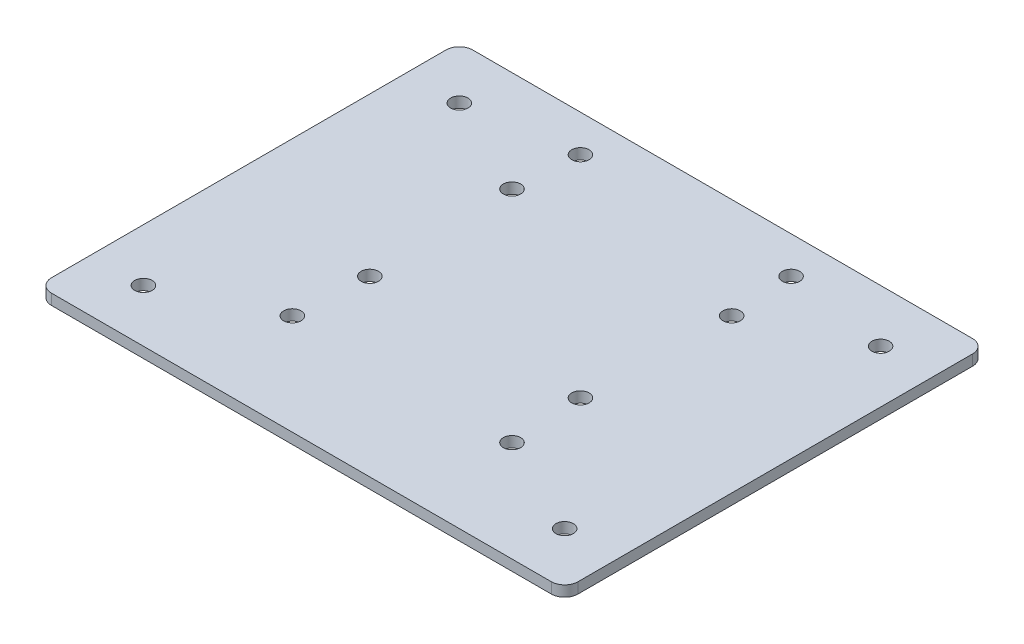
SolidWorks part; units mm, degrees
ref_plane "Front Plane" through (0, 0, 0) normal (0, 0, 1) x (1, 0, 0)
ref_plane "Top Plane" through (0, 0, 0) normal (0, 1, 0) x (1, 0, 0)
ref_plane "Right Plane" through (0, 0, 0) normal (1, 0, 0) x (0, 0, -1)
sketch "Sketch1" plane through (0, 0, 0) normal (0, 1, 0) x (1, 0, 0)
  line L0 (-36.5306, 28.4694) -> (-36.5306, -51.5306) construction
  line L1 (-46.5306, 28.4694) -> (53.4694, 28.4694)
  line L2 (-46.5306, 28.4694) -> (-46.5306, -51.5306)
  line L3 (-46.5306, -51.5306) -> (53.4694, -51.5306)
  line L4 (53.4694, 28.4694) -> (53.4694, -51.5306)
  line L5 (3.4694, 28.4694) -> (3.4694, -51.5306) construction
  line L6 (-46.5306, -11.5306) -> (53.4694, -11.5306) construction
  line L7 (43.4694, 28.4694) -> (43.4694, -51.5306) construction
  line L8 (3.4694, -11.5306) -> (24.329, 9.329) construction
  line L9 (3.4694, -11.5306) -> (24.329, -32.3903) construction
  line L10 (3.4694, -11.5306) -> (-17.3903, -32.3903) construction
  line L11 (3.4694, -11.5306) -> (-17.3903, 9.329) construction
  circle A0 centre (-36.5306, 18.4694) radius 1.651
  circle A1 centre (-36.5306, -41.5306) radius 1.651
  circle A2 centre (3.4694, -11.5306) radius 29.5 construction
  circle A3 centre (-16.5306, 21.4694) radius 1.651
  circle A4 centre (23.4694, 21.4694) radius 1.651
  circle A5 centre (-16.5306, -18.5306) radius 1.651
  circle A6 centre (23.4694, -18.5306) radius 1.651
  circle A7 centre (-17.3903, 9.329) radius 1.651
  circle A8 centre (24.329, 9.329) radius 1.651
  circle A9 centre (43.4694, -41.5306) radius 1.651
  circle A10 centre (43.4694, 18.4694) radius 1.651
  circle A11 centre (-17.3903, -32.3903) radius 1.651
  circle A12 centre (24.329, -32.3903) radius 1.651
  dimension "D4" = 3.302
  dimension "D5" = 10
  dimension "D6" = 10
  dimension "D7" = 3.302
  dimension "D8" = 59
  dimension "D9" = 3.302
  dimension "D10" = 3.302
  dimension "D11" = 7
  dimension "D12" = 7
  dimension "D13" = 20
  dimension "D14" = 20
  dimension "D16" = 3.302
  dimension "D17" = 3.302
  dimension "D18" = 3.302
  dimension "D19" = 3.302
  dimension "D20" = 3.302
  dimension "D21" = 3.302
  dimension "D22" = 45
  dimension "D1" = 100
  dimension "D2" = 80
  dimension "D3" = 10
  dimension "D15" = 40
  dimension "D23" = 45
  dimension "D24" = 45
  dimension "D25" = 45
extrude "Boss-Extrude1" add sketch "Sketch1" along normal blind 2.032
fillet "Fillet1" radius 2.54 1 edges at (-46.5306, 1.016, 51.5306)
fillet "Fillet2" radius 2.54 3 edges at (-46.5306, 1.016, -28.4694) (53.4694, 1.016, -28.4694) (53.4694, 1.016, 51.5306)
